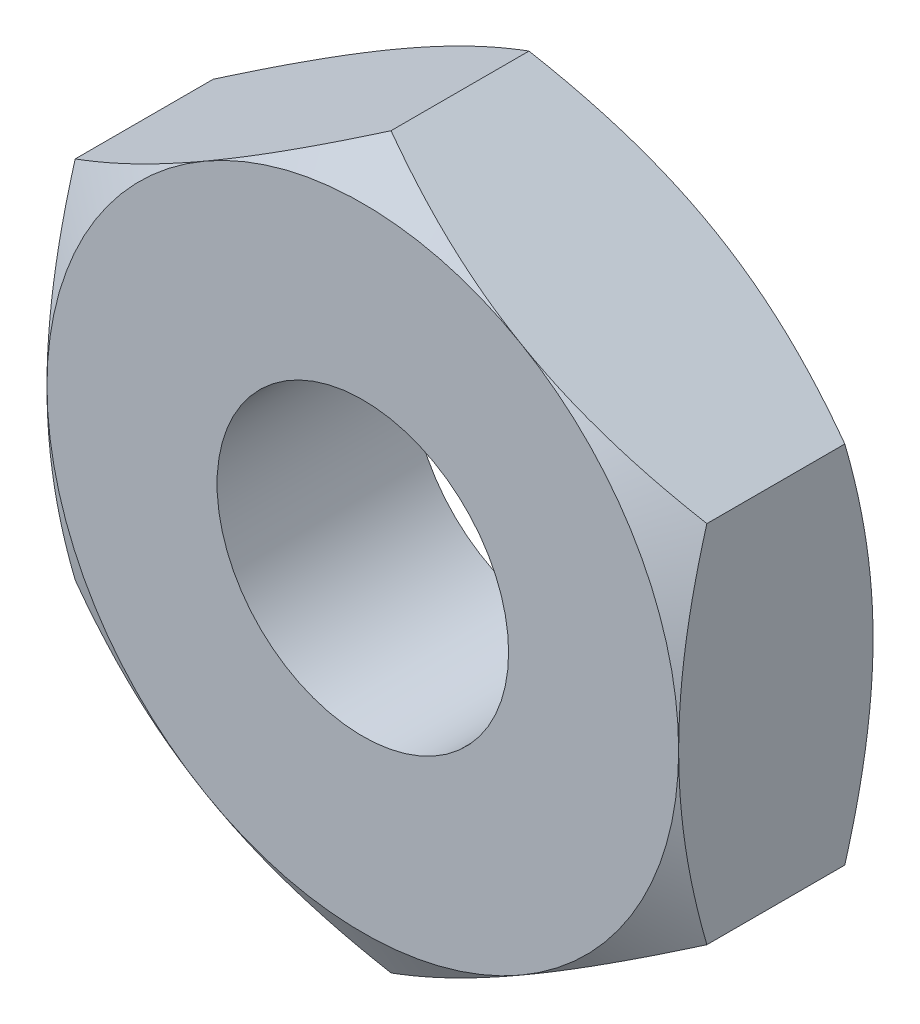
SolidWorks part; units mm, degrees
ref_plane "Front Plane" through (0, 0, 0) normal (0, 0, 1) x (1, 0, 0)
ref_plane "Top Plane" through (0, 0, 0) normal (0, 1, 0) x (1, 0, 0)
ref_plane "Right Plane" through (0, 0, 0) normal (1, 0, 0) x (0, 0, -1)
sketch "Sketch1" plane through (0, 0, 0) normal (0, 0, 1) x (1, 0, 0)
  line L1 (0, 15.0111) -> (-13, 7.5056)
  line L2 (-13, 7.5056) -> (-13, -7.5056)
  line L3 (-13, -7.5056) -> (0, -15.0111)
  line L4 (0, -15.0111) -> (13, -7.5056)
  line L5 (13, -7.5056) -> (13, 7.5056)
  line L6 (13, 7.5056) -> (0, 15.0111)
  circle A0 centre (0, 0) radius 13 construction
  circle A1 centre (0, 0) radius 6
  point P1 (13, 0)
  point P10 (-13, 0)
  dimension "D2" = 12
  dimension "D1" = 26
extrude "Boss-Extrude1" add sketch "Sketch1" along normal blind 8
sketch "Sketch3" plane through (0, 0, 0) normal (1, 0, 0) x (0, 0, -1)
  line L0 (-11.1053, 0) -> (-4.1254, 0) construction
  line L1 (-8, 15.0111) -> (-8, 12.0111)
  line L2 (-8, 7.5056) -> (-8, 15.0111) construction
  line L3 (-8, 15.0111) -> (0, 15.0111) construction
  line L4 (-8, 12.0111) -> (-5, 15.0111)
  line L5 (-5, 15.0111) -> (-8, 15.0111)
  dimension "D1" = 3
  dimension "D2" = 3
sketch "Sketch5" plane through (0, 0, 0) normal (0, 0, -1) x (-1, 0, 0)
  circle A0 centre (0, 0) radius 13
extrude "Cut-Extrude5" cut sketch "Sketch5" against normal blind 16 draft 60 flip side to cut
sketch "Sketch6" plane through (0, 0, 8) normal (0, 0, 1) x (1, 0, 0)
  circle A0 centre (0, 0) radius 13
extrude "Cut-Extrude6" cut sketch "Sketch6" against normal blind 16 draft 60 flip side to cut
